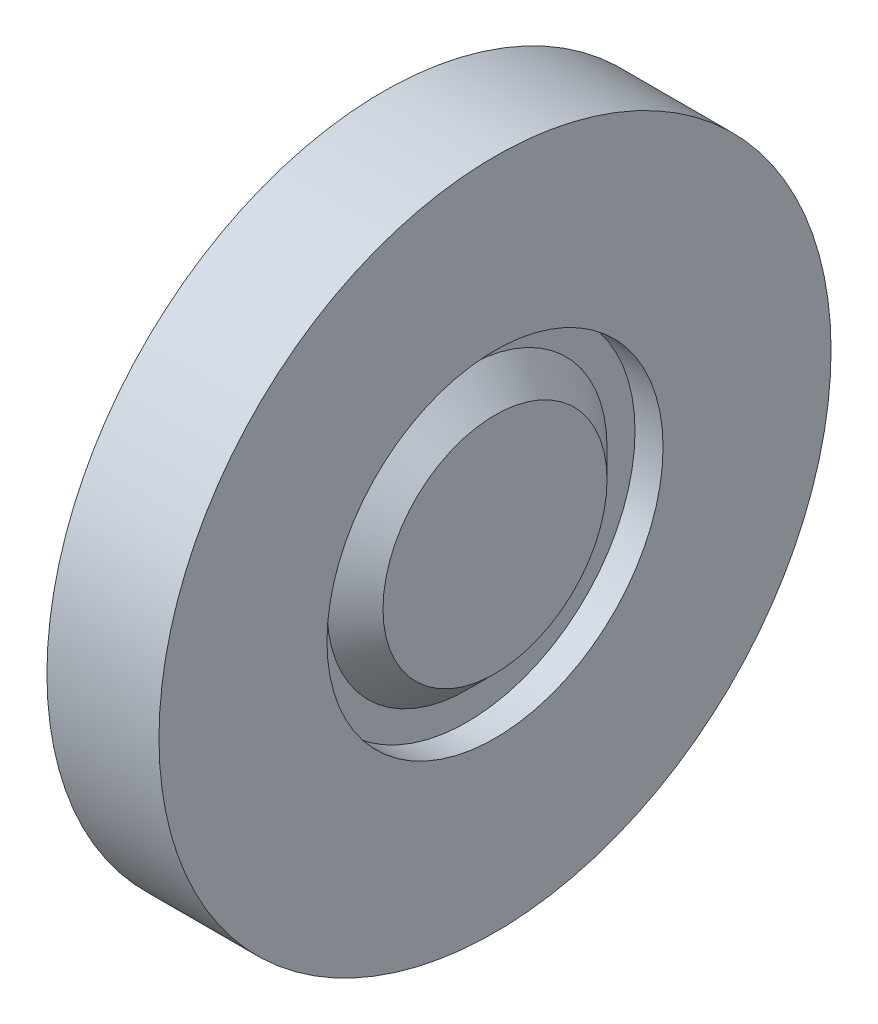
SolidWorks part; units mm, degrees
ref_plane "Front Plane" through (0, 0, 0) normal (0, 0, 1) x (1, 0, 0)
ref_plane "Top Plane" through (0, 0, 0) normal (0, 1, 0) x (1, 0, 0)
ref_plane "Right Plane" through (0, 0, 0) normal (1, 0, 0) x (0, 0, -1)
sketch "Sketch1" plane through (0, 0, 0) normal (1, 0, 0) x (0, 0, -1)
  circle A1 centre (0, 0) radius 6
extrude "Boss-Extrude1" add sketch "Sketch1" along normal blind 2
sketch "Sketch2" plane through (0, 0, 0) normal (-1, 0, 0) x (0, 0, 1)
  circle A0 centre (0, 0) radius 0.7
extrude "Cut-Extrude1" cut sketch "Sketch2" against normal blind 0.5
sketch "Sketch3" plane through (2, 0, 0) normal (1, 0, 0) x (0, 0, -1)
  circle A0 centre (0, 0) radius 3
extrude "Cut-Extrude2" cut sketch "Sketch3" against normal blind 0.5
sketch "Sketch4" plane through (1.5, 0, 0) normal (1, 0, 0) x (0, 0, -1)
  circle A0 centre (0, 0) radius 2.5
sketch "Sketch5" plane through (2, 0, 0) normal (1, 0, 0) x (0, 0, -1)
  circle A0 centre (0, 0) radius 2
loft "Loft1" add profiles "Sketch5", "Sketch4"
